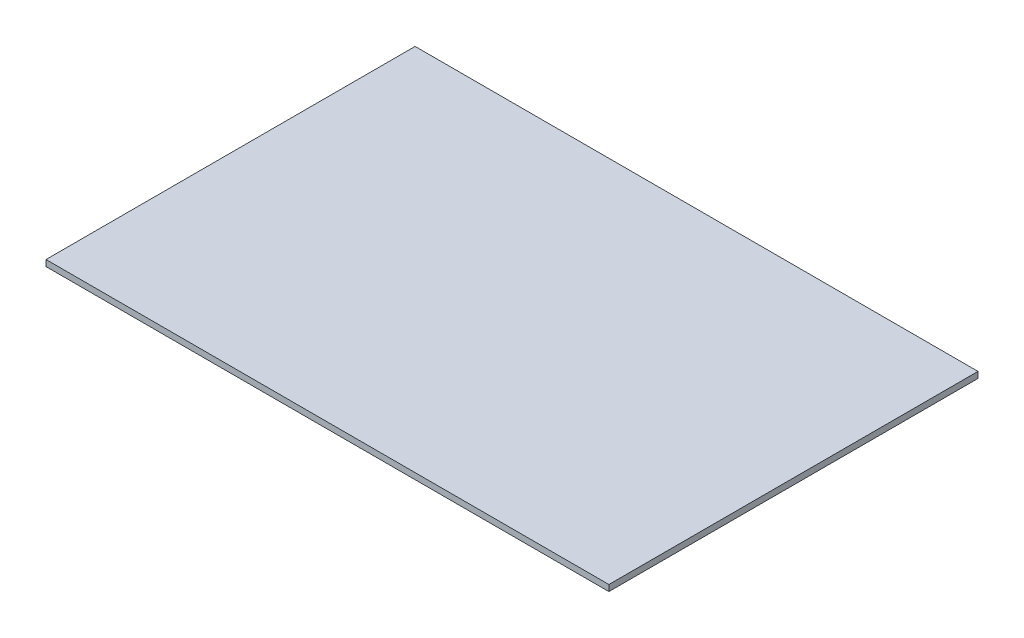
SolidWorks part; units mm, degrees
ref_plane "Front Plane" through (0, 0, 0) normal (0, 0, 1) x (1, 0, 0)
ref_plane "Top Plane" through (0, 0, 0) normal (0, 1, 0) x (1, 0, 0)
ref_plane "Right Plane" through (0, 0, 0) normal (1, 0, 0) x (0, 0, -1)
sketch "Sketch1" plane through (0, 0, 0) normal (0, 1, 0) x (1, 0, 0)
  line L1 (0, 0) -> (-914.4, 0)
  line L2 (0, 0) -> (0, -599.6)
  line L3 (0, -599.6) -> (-914.4, -599.6)
  line L4 (-914.4, 0) -> (-914.4, -599.6)
  dimension "D1" = 914.4
  dimension "D2" = 599.6
extrude "Boss-Extrude1" add sketch "Sketch1" along normal blind 10
